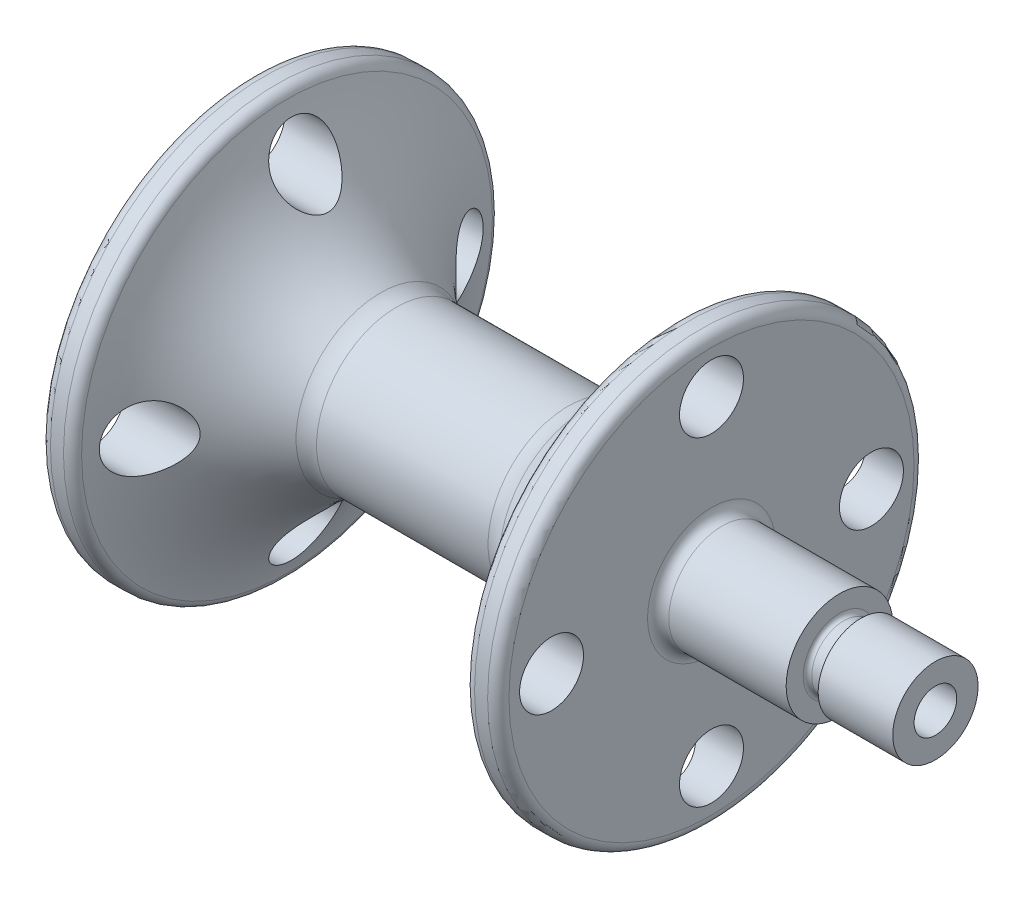
SolidWorks part; units mm, degrees
ref_plane "Front Plane" through (0, 0, 0) normal (0, 0, 1) x (1, 0, 0)
ref_plane "Top Plane" through (0, 0, 0) normal (0, 1, 0) x (1, 0, 0)
ref_plane "Right Plane" through (0, 0, 0) normal (1, 0, 0) x (0, 0, -1)
sketch "Sketch1" plane through (0, 0, 0) normal (0, 0, 1) x (1, 0, 0)
  line L0 (-36, 5) -> (-28, 5)
  line L1 (-28, 5) -> (-28, 20)
  line L2 (-28, 20) -> (-25, 20)
  line L3 (-25, 20) -> (-25, 7.5)
  line L4 (-25, 7.5) -> (12, 7.5)
  line L5 (12, 7.5) -> (12, 20)
  line L6 (12, 20) -> (15, 20)
  line L7 (15, 20) -> (15, 5)
  line L8 (15, 5) -> (27, 5)
  line L9 (27, 5) -> (27, 3)
  line L10 (27, 3) -> (29, 3)
  line L11 (29, 3) -> (29, 4)
  line L12 (29, 4) -> (36, 4)
  line L13 (36, 4) -> (36, 0)
  line L14 (-36, 5) -> (-36, 0)
  line L15 (-36, 0) -> (36, 0)
  line L16 (0, 0) -> (0, 30.1035) construction
  point P16 (28, 3)
  dimension "D1" = 4
  dimension "D2" = 72
  dimension "D3" = 7
  dimension "D4" = 2
  dimension "D5" = 12
  dimension "D6" = 3
  dimension "D7" = 3
  dimension "D8" = 8
  dimension "D9" = 20
  dimension "D10" = 5
  dimension "D11" = 7.5
  dimension "D12" = 5
  dimension "D13" = 3
revolve "Revolve1" add sketch "Sketch1" angle 360 about L15
sketch "Sketch2" plane through (0, 0, 0) normal (0, 0, 1) x (1, 0, 0)
  line L0 (12, 20) -> (12, -20) construction
  line L1 (12, 7.5) -> (-25, 7.5) construction
  line L2 (-25, -20) -> (-25, 20) construction
  line L3 (12, 20) -> (12, 7.5)
  line L4 (12, 7.5) -> (2.3174, 7.5)
  line L5 (-25, 7.5) -> (-25, 20)
  line L6 (-15.3174, 7.5) -> (-25, 7.5)
  line L7 (0, 0) -> (-36.766, 0) construction
  arc A0 (-25, 20) -> (-15.3174, 7.5) centre (-6.5, 24.3301) ccw
  arc A1 (2.3174, 7.5) -> (12, 20) centre (-6.5, 24.3301) ccw
  dimension "D1" = 38
revolve "Revolve2" add sketch "Sketch2" angle 360 about L7
fillet "Fillet1" radius 3 2 edges at (-15.3174, 0, -7.5) (2.3174, 0, -7.5)
fillet "Fillet2" radius 0.4 2 edges at (29, 0, 3) (27, 0, 3)
fillet "Fillet3" radius 1 1 edges at (-28, 0, 5)
fillet "Fillet4" radius 1 1 edges at (15, 0, 5)
fillet "Fillet5" radius 1 4 edges at (-28, 0, 20) (-25, 0, -20) (15, 0, 20) (12, 0, 20)
hole_wizard "Hole1" positions "Sketch3" profile "Sketch4" legacy end condition through all
sketch "Sketch3" plane through (-28, 0, 0) normal (-1, 0, 0) x (0, 0, 1)
  point P0 (15, 0)
  point P4 (0, 0)
  dimension "D1" = 15
sketch "Sketch4" plane through (-28, 0, 15) normal (0, 1, 0) x (0, 0, 1)
  line L0 (0, 0) -> (0, 64)
  line L1 (0, 64) -> (3, 64)
  line L2 (3, 64) -> (3, 0)
  line L3 (3, 0) -> (0, 0)
  line L4 (0, 110) -> (0, -10) construction
  dimension "Diameter" = 6
  dimension "Depth" = 64
pattern_circular "CirPattern1" count 4 over 360 about axis through (0, 0, 0) along (1, 0, 0) of "Hole1"
hole_wizard "Hole2" positions "Sketch5" profile "Sketch6" legacy end condition through all
sketch "Sketch5" plane through (-36, 0, 0) normal (-1, 0, 0) x (0, 0, 1)
  point P0 (0, 0)
sketch "Sketch6" plane through (-36, 0, 0) normal (0, 1, 0) x (0, 0, 1)
  line L0 (0, 0) -> (0, 72)
  line L1 (0, 72) -> (2, 72)
  line L2 (2, 72) -> (2, 0)
  line L3 (2, 0) -> (0, 0)
  line L4 (0, 110) -> (0, -10) construction
  dimension "Diameter" = 4
  dimension "Depth" = 72
